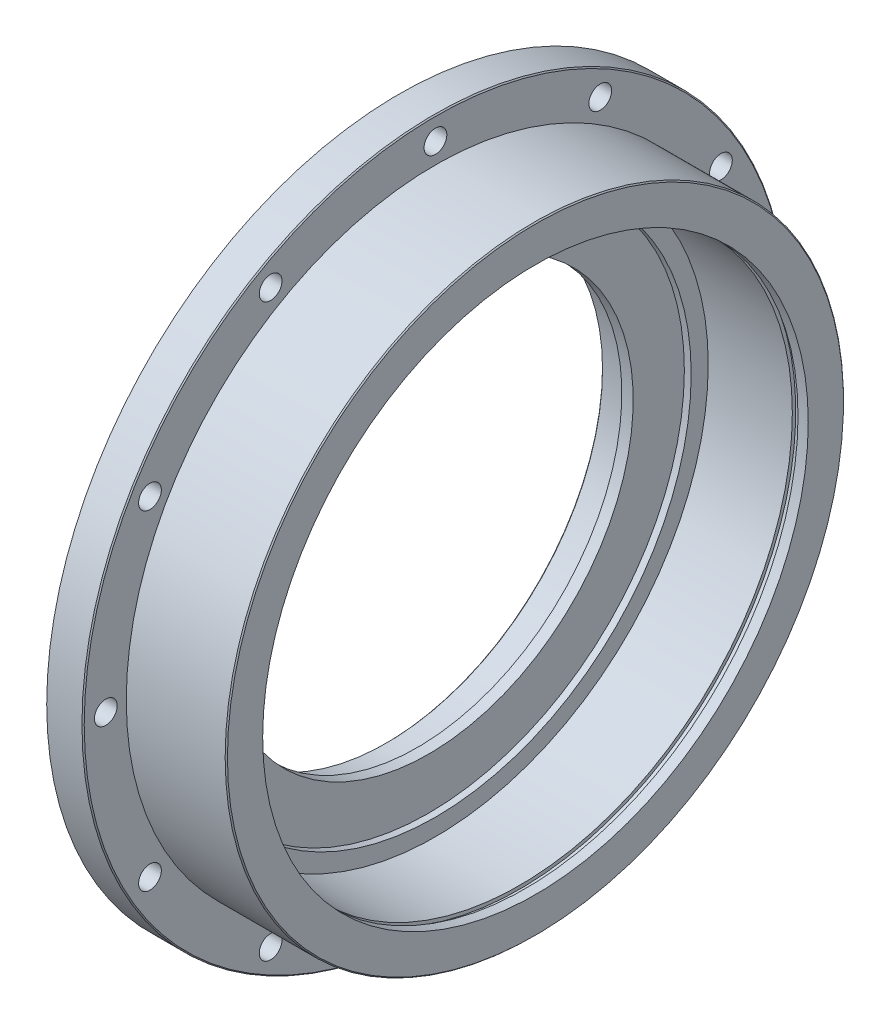
SolidWorks part; units mm, degrees
ref_plane "前视基准面" through (0, 0, 0) normal (0, 0, 1) x (1, 0, 0)
ref_plane "上视基准面" through (0, 0, 0) normal (0, 1, 0) x (1, 0, 0)
ref_plane "右视基准面" through (0, 0, 0) normal (1, 0, 0) x (0, 0, -1)
other "Configuration Table"
sketch "草图1" plane through (0, 0, 0) normal (0, 0, 1) x (1, 0, 0)
  line L0 (0, 0) -> (0, 120)
  line L1 (0, 120) -> (6, 120)
  line L2 (6, 120) -> (6, 155)
  line L3 (6, 155) -> (22, 155)
  line L4 (22, 155) -> (22, 136)
  line L5 (22, 136) -> (66, 136)
  line L6 (66, 136) -> (66, 0)
  line L7 (66, 0) -> (0, 0)
  line L8 (0, 0) -> (242.3465, 0) construction
  dimension "D1" = 240
  dimension "D2" = 310
  dimension "D3" = 272
  dimension "D4" = 6
  dimension "D5" = 16
  dimension "D6" = 66
revolve "旋转1" add sketch "草图1" angle 360 about L8
sketch "草图2" plane through (0, 0, 0) normal (0, 0, 1) x (1, 0, 0)
  line L0 (0, 0) -> (111.2262, 0) construction
  line L1 (66, -136) -> (66, 136) construction
  line L2 (0, 0) -> (0, 95)
  line L3 (0, 120) -> (0, -120) construction
  line L4 (0, 95) -> (14, 95)
  line L5 (14, 95) -> (14, 90)
  line L6 (14, 90) -> (19, 90)
  line L7 (19, 90) -> (19, 112.5)
  line L8 (19, 112.5) -> (22, 112.5)
  line L9 (22, -136) -> (22, 136) construction
  line L10 (22, 112.5) -> (22, 120)
  line L11 (22, 120) -> (59, 120)
  line L12 (59, 120) -> (59, 121.5)
  line L13 (59, 121.5) -> (61.5, 121.5)
  line L14 (61.5, 121.5) -> (61.5, 120)
  line L15 (61.5, 120) -> (66, 120)
  line L16 (66, 120) -> (66, 0)
  line L18 (0, 0) -> (66, 0)
  dimension "D1" = 190
  dimension "D2" = 180
  dimension "D3" = 225
  dimension "D4" = 240
  dimension "D5" = 243
  dimension "D6" = 14
  dimension "D7" = 5
  dimension "D8" = 4.5
  dimension "D9" = 7
revolve "切除-旋转1" cut sketch "草图2" angle 360 about L0
sketch "草图3" plane through (6, 0, 0) normal (-1, 0, 0) x (0, 0, 1)
  circle A0 centre (0, 0) radius 145 construction
  circle A1 centre (0, 145) radius 5
  circle A2 centre (72.5, 125.5737) radius 5
  circle A3 centre (125.5737, 72.5) radius 5
  circle A4 centre (145, 0) radius 5
  circle A5 centre (125.5737, -72.5) radius 5
  circle A6 centre (72.5, -125.5737) radius 5
  circle A7 centre (0, -145) radius 5
  circle A8 centre (-72.5, -125.5737) radius 5
  circle A9 centre (-125.5737, -72.5) radius 5
  circle A10 centre (-145, 0) radius 5
  circle A11 centre (-125.5737, 72.5) radius 5
  circle A12 centre (-72.5, 125.5737) radius 5
  point P5 (-58.4773, 123.6778)
  point P6 (0, 0)
  point P30 (0, 0)
  dimension "D1" = 290
  dimension "D2" = 10
  dimension "D3" = 12
extrude "切除-拉伸1" cut sketch "草图3" against normal through all
chamfer "倒角1" distance 0.5 angle 45 3 edges at (66, 0, 136) (22, 0, 155) (0, 0, 95)
